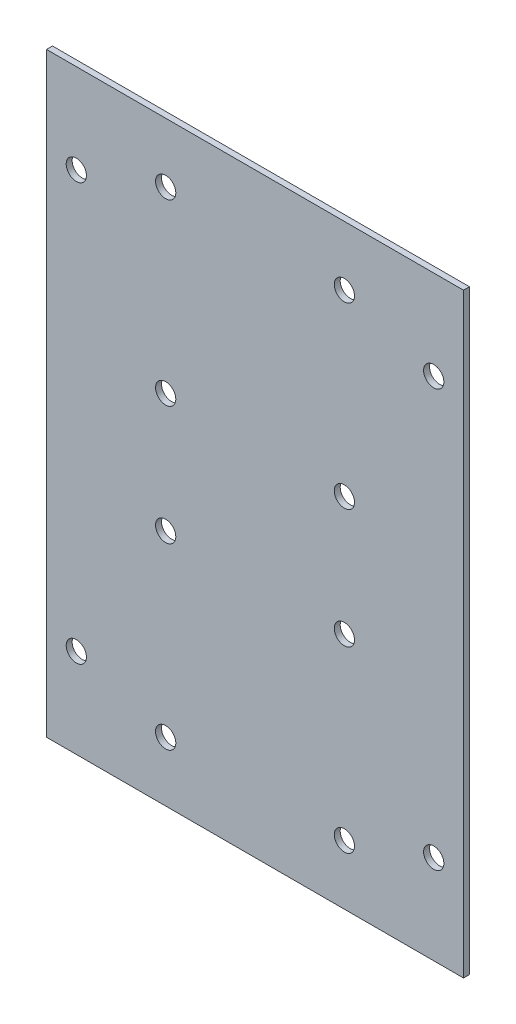
SolidWorks part; units mm, degrees
ref_plane "Front Plane" through (0, 0, 0) normal (0, 0, 1) x (1, 0, 0)
ref_plane "Top Plane" through (0, 0, 0) normal (0, 1, 0) x (1, 0, 0)
ref_plane "Right Plane" through (0, 0, 0) normal (1, 0, 0) x (0, 0, -1)
sketch "Sketch1" plane through (0, 0, 0) normal (0, 0, 1) x (1, 0, 0)
  line L1 (-35, -50) -> (35, -50)
  line L2 (-35, -50) -> (-35, 50)
  line L3 (-35, 50) -> (35, 50)
  line L4 (35, -50) -> (35, 50)
  line L5 (-35, -50) -> (35, 50) construction
  line L6 (-35, 50) -> (35, -50) construction
  point P0 (0, 0)
extrude "Boss-Extrude1" add sketch "Sketch1" against normal blind 1
sketch "Sketch2" plane through (0, 0, 0) normal (0, 0, 1) x (1, 0, 0)
  circle A0 centre (-30, -35) radius 1.7
  circle A1 centre (-30, 35) radius 1.7
  circle A2 centre (30, -35) radius 1.7
  circle A3 centre (30, 35) radius 1.7
  circle A4 centre (-15, -40) radius 1.7
  circle A5 centre (-15, -10) radius 1.7
  circle A6 centre (-15, 10) radius 1.7
  circle A7 centre (-15, 40) radius 1.7
  circle A8 centre (15, -40) radius 1.7
  circle A9 centre (15, -10) radius 1.7
  circle A10 centre (15, 10) radius 1.7
  circle A11 centre (15, 40) radius 1.7
extrude "Cut-Extrude1" cut sketch "Sketch2" along normal through all and the other way through all
